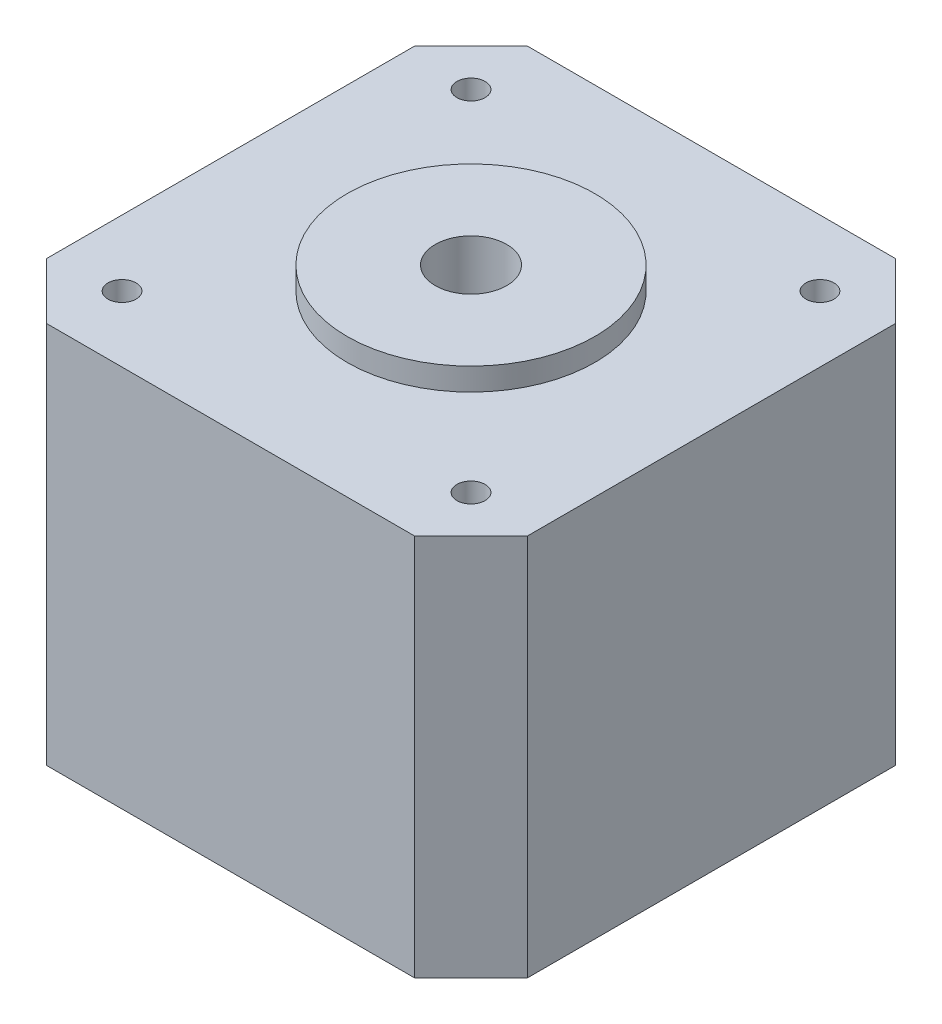
SolidWorks part; units mm, degrees
ref_plane "Front Plane" through (0, 0, 0) normal (0, 0, 1) x (1, 0, 0)
ref_plane "Top Plane" through (0, 0, 0) normal (0, 1, 0) x (1, 0, 0)
ref_plane "Right Plane" through (0, 0, 0) normal (1, 0, 0) x (0, 0, -1)
sketch "Sketch1" plane through (0, 0, 0) normal (0, 1, 0) x (1, 0, 0)
  line L1 (-21.35, -21.35) -> (21.35, -21.35)
  line L2 (-21.35, -21.35) -> (-21.35, 21.35)
  line L3 (-21.35, 21.35) -> (21.35, 21.35)
  line L4 (21.35, -21.35) -> (21.35, 21.35)
  line L5 (-21.35, -21.35) -> (21.35, 21.35) construction
  line L6 (-21.35, 21.35) -> (21.35, -21.35) construction
  point P0 (0, 0)
  dimension "D1" = 42.7
  dimension "D2" = 42.7
extrude "Boss-Extrude1" add sketch "Sketch1" along normal blind 34
sketch "Sketch2" plane through (0, 34, 0) normal (0, 1, 0) x (1, 0, 0)
  circle A0 centre (0, 0) radius 11
  dimension "D1" = 22
extrude "Boss-Extrude2" add sketch "Sketch2" along normal blind 2
sketch "Sketch3" plane through (0, 36, 0) normal (0, 1, 0) x (1, 0, 0)
  circle A0 centre (0, 0) radius 3.175
  dimension "D1" = 6.35
extrude "Cut-Extrude1" cut sketch "Sketch3" against normal through all
hole_wizard "M3 Tapped Hole1" positions "Sketch4" profile "Sketch5" tap size "M3" standard "ISO"
sketch "Sketch4" plane through (0, 34, 0) normal (0, 1, 0) x (1, 0, 0)
  line L1 (-15.5, -15.5) -> (15.5, -15.5)
  line L2 (-15.5, -15.5) -> (-15.5, 15.5)
  line L3 (-15.5, 15.5) -> (15.5, 15.5)
  line L4 (15.5, -15.5) -> (15.5, 15.5)
  line L5 (-15.5, -15.5) -> (15.5, 15.5) construction
  line L6 (-15.5, 15.5) -> (15.5, -15.5) construction
  point P2 (15.5, 15.5)
  point P73 (-15.5, -15.5)
  point P74 (-15.5, 15.5)
  point P75 (15.5, -15.5)
  dimension "D1" = 31
sketch "Sketch5" plane through (15.5, 34, -15.5) normal (1, 0, 0) x (0, 0, 1)
  line L0 (0, 0) -> (0, 8.2511)
  line L1 (0, 8.2511) -> (1.25, 7.5)
  line L2 (1.25, 7.5) -> (1.25, 0)
  line L5 (1.25, 0) -> (0, 0)
  line L10 (0, 8.2511) -> (-1.25, 7.5) construction
  line L11 (0, -6.35) -> (0, 107.95) construction
  dimension "Tap Drill Dia." = 2.5
  dimension "Tap Drill Depth" = 7.5
  dimension "Drill Angle" = 118
cosmetic thread "Hole Thread1" parameters "D1"=6, "D2"=3
cosmetic thread "Hole Thread2" parameters "D1"=6, "D2"=3
cosmetic thread "Hole Thread3" parameters "D1"=6, "D2"=3
cosmetic thread "Hole Thread4" parameters "D1"=6, "D2"=3
chamfer "Chamfer1" distance 5 angle 45 4 edges at (-21.35, 17, 21.35) (21.35, 17, 21.35) (21.35, 17, -21.35) (-21.35, 17, -21.35)
